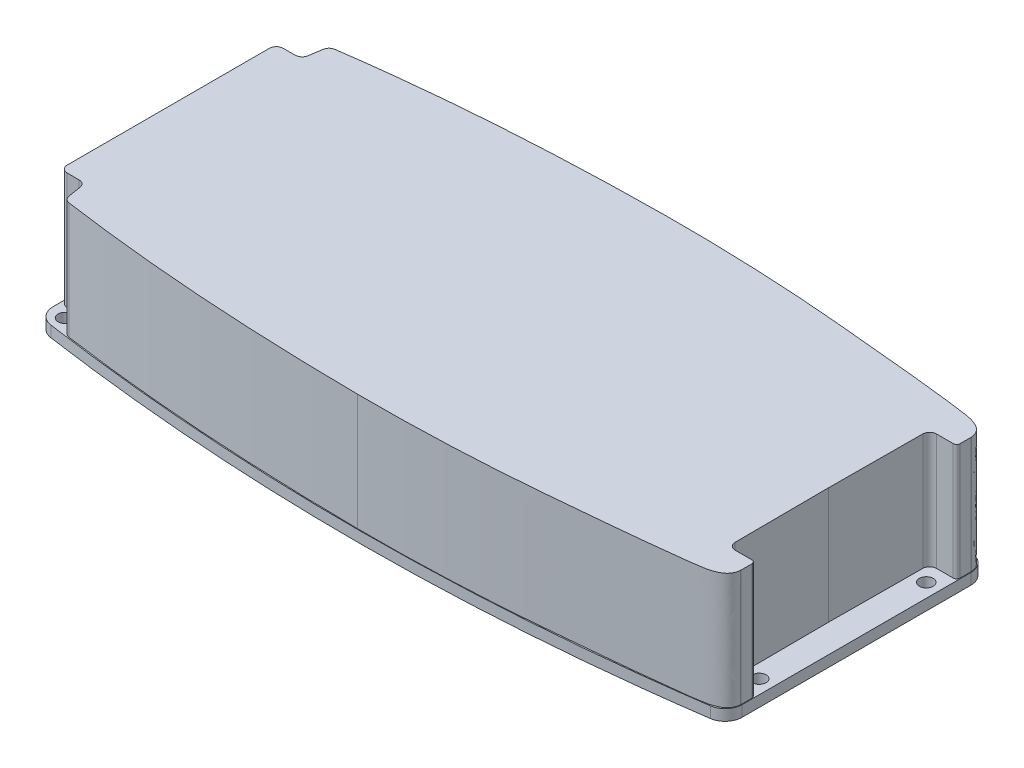
SolidWorks part; units mm, degrees
ref_plane "Front Plane" through (0, 0, 0) normal (0, 0, 1) x (1, 0, 0)
ref_plane "Top Plane" through (0, 0, 0) normal (0, 1, 0) x (1, 0, 0)
ref_plane "Right Plane" through (0, 0, 0) normal (1, 0, 0) x (0, 0, -1)
sketch "Sketch1" plane through (0, 0, 0) normal (0, 1, 0) x (1, 0, 0)
  line L0 (0, 0) -> (0, 45) construction
  line L1 (0, 0) -> (0, -45) construction
  line L2 (0, 0) -> (100, 0) construction
  line L3 (0, 0) -> (-100, 0) construction
  line L4 (-100, 33.1804) -> (-100, -33.1804)
  line L5 (100, 33.1804) -> (100, -33.1804)
  arc A0 (95.7105, -38.1296) -> (100, -33.1804) centre (95, -33.1804) ccw
  arc A1 (100, 33.1804) -> (95.7105, 38.1296) centre (95, 33.1804) ccw
  arc A2 (-95.7105, -38.1296) -> (-100, -33.1804) centre (-95, -33.1804) cw
  arc A3 (-95.7105, 38.1296) -> (-100, 33.1804) centre (-95, 33.1804) ccw
  spline S0 degree 3 poles (-95.7105, 38.1296) (-63.807, 42.7099) (0, 47.2901) (63.807, 42.7099) (95.7105, 38.1296) knots 0.021447 0.021447 0.021447 0.021447 0.5 0.978553 0.978553 0.978553 0.978553
  spline S1 degree 3 poles (-95.7105, -38.1296) (-63.807, -42.7099) (0, -47.2901) (63.807, -42.7099) (95.7105, -38.1296) knots 0.021447 0.021447 0.021447 0.021447 0.5 0.978553 0.978553 0.978553 0.978553
  dimension "D1" = 5
extrude "Boss-Extrude1" add sketch "Sketch1" along normal blind 3.2
sketch "Sketch4" plane through (0, 0, 0) normal (0, 1, 0) x (1, 0, 0)
  line L0 (-99.75, 0) -> (-123.1155, 0) construction
  line L1 (99.8366, -33.3874) -> (99.8366, -30.4288)
  line L2 (-99.75, 29.3506) -> (-99.75, -29.3506)
  line L4 (-97.7499, -31.3506) -> (-94.2724, -31.3504)
  line L5 (-92.2975, -33.0338) -> (-91.6747, -36.9182)
  line L6 (99.8366, -30.4288) -> (99.8366, -30.222)
  line L7 (0, 0) -> (0, -60.4552) construction
  line L8 (98.8366, -29.222) -> (93.9916, -29.222)
  line L9 (91.9917, -27.2333) -> (91.8366, 0)
  line L11 (91.9917, 27.2333) -> (91.8366, 0)
  line L12 (98.8366, 29.222) -> (93.9916, 29.222)
  line L13 (99.8366, 30.4288) -> (99.8366, 30.222)
  line L14 (-92.2975, 33.0338) -> (-91.6747, 36.9182)
  line L15 (-97.7499, 31.3506) -> (-94.2724, 31.3504)
  line L16 (99.8366, 33.3874) -> (99.8366, 30.4288)
  arc A0 (98.8366, -29.222) -> (99.8366, -30.222) centre (98.8366, -30.222) cw
  arc A1 (93.9916, -29.222) -> (91.9917, -27.2333) centre (93.9916, -27.222) cw
  arc A2 (99.8292, -33.5596) -> (99.8366, -33.3874) centre (97.8366, -33.3874) ccw
  arc A3 (-91.6747, -36.9182) -> (-89.9822, -38.5815) centre (-89.6999, -36.6016) ccw
  arc A4 (-94.2724, -31.3504) -> (-92.2975, -33.0338) centre (-94.2723, -33.3504) cw
  arc A5 (-99.75, -29.3506) -> (-97.7499, -31.3506) centre (-97.75, -29.3506) ccw
  arc A6 (-99.75, 29.3506) -> (-97.7499, 31.3506) centre (-97.75, 29.3506) cw
  arc A7 (-94.2724, 31.3504) -> (-92.2975, 33.0338) centre (-94.2723, 33.3504) ccw
  arc A8 (-91.6747, 36.9182) -> (-89.9822, 38.5815) centre (-89.6999, 36.6016) cw
  arc A9 (99.8292, 33.5596) -> (99.8366, 33.3874) centre (97.8366, 33.3874) cw
  arc A10 (93.9916, 29.222) -> (91.9917, 27.2333) centre (93.9916, 27.222) ccw
  arc A11 (98.8366, 29.222) -> (99.8366, 30.222) centre (98.8366, 30.222) ccw
  spline S0 degree 3 poles (-89.9822, -38.5815) (-75.4234, -40.6571) (-45.867, -43.6341) (-15.4347, -44.6691) (0, -44.8028) knots 0.011824 0.011824 0.011824 0.011824 0.505912 1 1 1 1
  spline S1 degree 3 poles (0, -44.8028) (13.8366, -44.9145) (34.369, -44.2563) (64.9951, -41.4301) (81.2001, -39.9459) (95.3645, -38.0697) (98.6812, -36.554) (99.7218, -34.8016) (99.8292, -33.5596) knots 0 0 0 0 0.456143 0.54938 0.889817 0.935788 0.96653 0.999161 0.999161 0.999161 0.999161
  spline S2 degree 3 poles (0, 44.8028) (13.8366, 44.9145) (34.369, 44.2563) (64.9951, 41.4301) (81.2001, 39.9459) (95.3645, 38.0697) (98.6812, 36.554) (99.7218, 34.8016) (99.8292, 33.5596) knots 0 0 0 0 0.456143 0.54938 0.889817 0.935788 0.96653 0.999161 0.999161 0.999161 0.999161
  spline S3 degree 3 poles (-89.9822, 38.5815) (-75.4234, 40.6571) (-45.867, 43.6341) (-15.4347, 44.6691) (0, 44.8028) knots 0.011824 0.011824 0.011824 0.011824 0.505912 1 1 1 1
  point P60 (-99.75, 0)
  dimension "D1" = 1
  dimension "D2" = 2
  dimension "D3" = 2
extrude "Boss-Extrude2" add sketch "Sketch4" along normal blind 37 separate body
sketch "Sketch5" plane through (0, 3.2, 0) normal (0, 1, 0) x (1, 0, 0)
  line L0 (0, 0) -> (-139.9446, 0) construction
  circle A0 centre (-95.4527, 34.2879) radius 2
  circle A1 centre (-95.4527, -34.2879) radius 2
  circle A2 centre (95.9905, 24.2357) radius 2
  circle A3 centre (95.9905, -24.2357) radius 2
extrude "Cut-Extrude1" cut sketch "Sketch5" against normal through all
